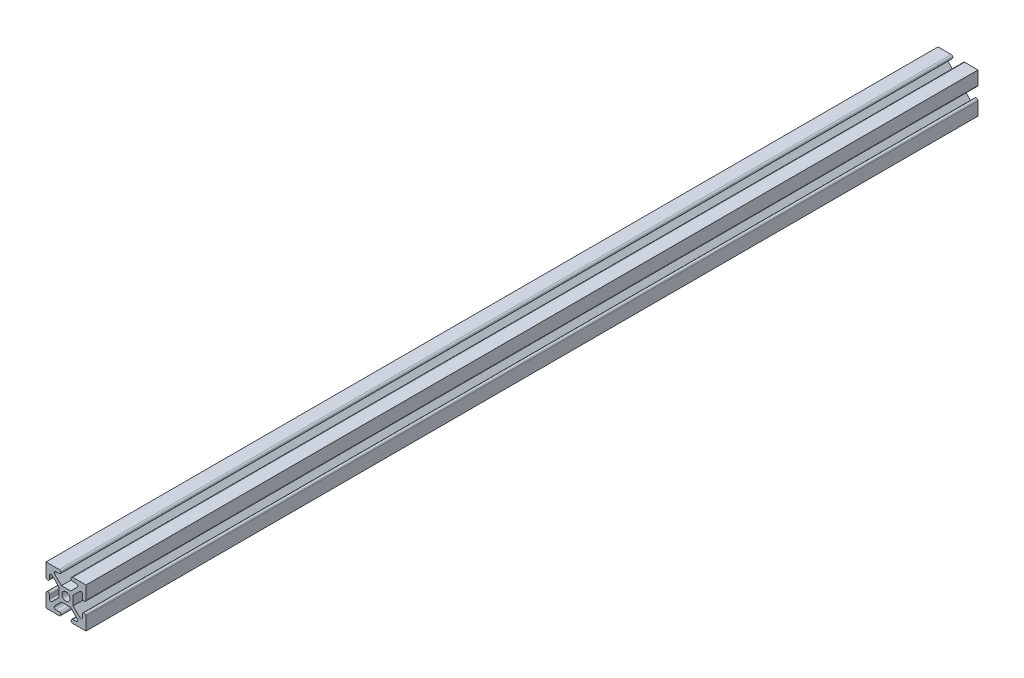
SolidWorks part; units mm, degrees
ref_plane "Front Plane" through (0, 0, 0) normal (0, 0, 1) x (1, 0, 0)
ref_plane "Top Plane" through (0, 0, 0) normal (0, 1, 0) x (1, 0, 0)
ref_plane "Right Plane" through (0, 0, 0) normal (1, 0, 0) x (0, 0, -1)
sketch "Sketch1" plane through (0, 0, 0) normal (0, 0, 1) x (1, 0, 0)
  line L2 (-12.7, -12.7) -> (-4.3434, -12.7)
  line L3 (-4.3434, -10.4902) -> (-6.4748, -10.4902)
  line L4 (-7.1932, -8.7558) -> (-2.9332, -4.4958)
  line L5 (-2.9332, -4.4958) -> (2.9332, -4.4958)
  line L6 (2.9332, -4.4958) -> (7.1932, -8.7558)
  line L7 (6.4748, -10.4902) -> (4.3434, -10.4902)
  line L8 (4.3434, -12.7) -> (12.7, -12.7)
  line L11 (12.7, -12.7) -> (12.7, -4.3434)
  line L12 (10.4902, -4.3434) -> (10.4902, -6.4748)
  line L13 (8.7558, -7.1932) -> (4.4958, -2.9332)
  line L14 (4.4958, -2.9332) -> (4.4958, 2.9332)
  line L15 (4.4958, 2.9332) -> (8.7558, 7.1932)
  line L16 (10.4902, 6.4748) -> (10.4902, 4.3434)
  line L17 (12.7, 4.3434) -> (12.7, 12.7)
  line L20 (12.7, 12.7) -> (4.3434, 12.7)
  line L21 (4.3434, 10.4902) -> (6.4748, 10.4902)
  line L22 (7.1932, 8.7558) -> (2.9332, 4.4958)
  line L23 (2.9332, 4.4958) -> (-2.9332, 4.4958)
  line L24 (-2.9332, 4.4958) -> (-7.1932, 8.7558)
  line L25 (-6.4748, 10.4902) -> (-4.3434, 10.4902)
  line L26 (-4.3434, 12.7) -> (-12.7, 12.7)
  line L29 (-12.7, 12.7) -> (-12.7, 4.3434)
  line L30 (-10.4902, 4.3434) -> (-10.4902, 6.4748)
  line L31 (-8.7558, 7.1932) -> (-4.4958, 2.9332)
  line L32 (-4.4958, 2.9332) -> (-4.4958, -2.9332)
  line L33 (-4.4958, -2.9332) -> (-8.7558, -7.1932)
  line L34 (-10.4902, -6.4748) -> (-10.4902, -4.3434)
  line L35 (-12.7, -4.3434) -> (-12.7, -12.7)
  circle A0 centre (0, 0) radius 2.6035
  arc A6 (-4.3434, -12.7) -> (-4.3434, -10.4902) centre (-4.3434, -11.5951) ccw
  arc A7 (-6.4748, -10.4902) -> (-7.1932, -8.7558) centre (-6.4748, -9.4742) cw
  arc A10 (7.1932, -8.7558) -> (6.4748, -10.4902) centre (6.4748, -9.4742) cw
  arc A11 (4.3434, -10.4902) -> (4.3434, -12.7) centre (4.3434, -11.5951) ccw
  arc A17 (12.7, -4.3434) -> (10.4902, -4.3434) centre (11.5951, -4.3434) ccw
  arc A18 (10.4902, -6.4748) -> (8.7558, -7.1932) centre (9.4742, -6.4748) cw
  arc A21 (8.7558, 7.1932) -> (10.4902, 6.4748) centre (9.4742, 6.4748) cw
  arc A22 (10.4902, 4.3434) -> (12.7, 4.3434) centre (11.5951, 4.3434) ccw
  arc A28 (4.3434, 12.7) -> (4.3434, 10.4902) centre (4.3434, 11.5951) ccw
  arc A29 (6.4748, 10.4902) -> (7.1932, 8.7558) centre (6.4748, 9.4742) cw
  arc A32 (-7.1932, 8.7558) -> (-6.4748, 10.4902) centre (-6.4748, 9.4742) cw
  arc A33 (-4.3434, 10.4902) -> (-4.3434, 12.7) centre (-4.3434, 11.5951) ccw
  arc A39 (-12.7, 4.3434) -> (-10.4902, 4.3434) centre (-11.5951, 4.3434) ccw
  arc A40 (-10.4902, 6.4748) -> (-8.7558, 7.1932) centre (-9.4742, 6.4748) cw
  arc A43 (-8.7558, -7.1932) -> (-10.4902, -6.4748) centre (-9.4742, -6.4748) cw
  arc A44 (-10.4902, -4.3434) -> (-12.7, -4.3434) centre (-11.5951, -4.3434) ccw
  point P2 (-12.7, 12.7)
  point P3 (-2.831, -4.4958)
  point P4 (-12.463, 12.7)
  point P5 (12.7, 12.7)
  point P6 (12.7, 12.4568)
  point P7 (12.7, -12.7)
  point P8 (12.7, -12.4104)
  point P9 (-12.7, -12.7)
  point P10 (-12.7, -12.3667)
  point P11 (-3.1221, -4.4958)
  point P12 (0, 0)
  point P13 (4.4958, -2.9303)
  point P21 (4.4929, -2.7389)
  point P22 (0, 0)
  point P25 (2.9332, 4.4958)
  point P26 (2.7504, 4.4958)
  point P34 (0, 0)
  point P35 (-4.4958, 2.9332)
  point P36 (-4.4958, 2.5336)
  point P37 (0, 0)
  point P101 (-4.4958, 0)
  point P102 (0, 4.4958)
  point P103 (4.4958, 0)
  point P104 (0, 0)
  point P127 (0, -4.4958)
extrude "Boss-Extrude1" add sketch "Sketch1" against normal blind 566.7375
